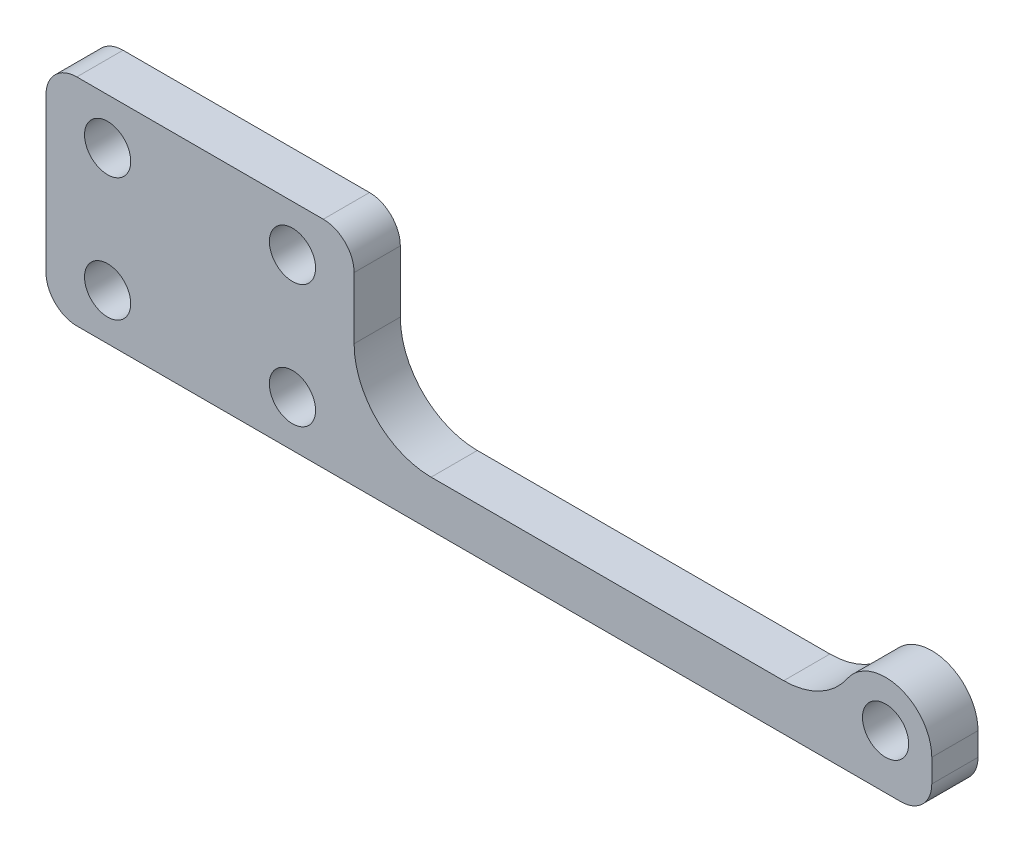
SolidWorks part; units mm, degrees
ref_plane "Płaszczyzna przednia" through (0, 0, 0) normal (0, 0, 1) x (1, 0, 0)
ref_plane "Płaszczyzna górna" through (0, 0, 0) normal (0, 1, 0) x (1, 0, 0)
ref_plane "Płaszczyzna prawa" through (0, 0, 0) normal (1, 0, 0) x (0, 0, -1)
sketch "Szkic1" plane through (0, 0, 0) normal (0, 0, 1) x (1, 0, 0)
  line L0 (10, -7) -> (47.5, -7)
  line L1 (10, -7) -> (-10, -7)
  line L2 (10, -7) -> (10, 7)
  line L3 (10, 7) -> (-10, 7)
  line L4 (-10, -7) -> (-10, 7)
  line L5 (10, -7) -> (-10, 7) construction
  line L6 (10, 7) -> (-10, -7) construction
  line L7 (47.5, -7) -> (47.5, -3.5)
  line L8 (10, -4) -> (41.542, -4)
  circle A0 centre (-6, 4) radius 1.5
  circle A1 centre (6, 4) radius 1.5
  circle A2 centre (6, -4) radius 1.5
  circle A3 centre (-6, -4) radius 1.5
  circle A4 centre (44.5, -3.5) radius 1.5
  arc A5 (47.5, -3.5) -> (41.542, -4) centre (44.5, -3.5) ccw
  point P2 (0, 0)
  point P21 (45.689, -2.6371)
  point P22 (0, 0)
  point P23 (45.314, -4)
  point P24 (7.1101, -1.6702)
  point P25 (9.0229, -3.5532)
  point P26 (-8.4816, -4.0194)
  point P27 (0, 0)
  point P28 (0, 0)
  point P29 (0, 0)
  point P30 (0, 0)
  dimension "D1" = 4
  dimension "D7" = 38.5
  dimension "D9" = 3
  dimension "D10" = 3
  dimension "D11" = 3
  dimension "D2" = 6
  dimension "D5" = 14
  dimension "D6" = 20
  dimension "D8" = 0.5
  dimension "D12" = 12
  dimension "D13" = 8
  dimension "D3" = 2
  dimension "D4" = 2
extrude "Dodanie-wyciągnięcie1" add sketch "Szkic1" along normal blind 3
fillet "Zaokrąglenie5" radius 2 4 edges at (-10, -7, 1.5) (-10, 7, 1.5) (10, 7, 1.5) (47.5, -7, 1.5)
fillet "Zaokrąglenie6" radius 5 2 edges at (41.542, -4, 1.5) (10, -4, 1.5)
